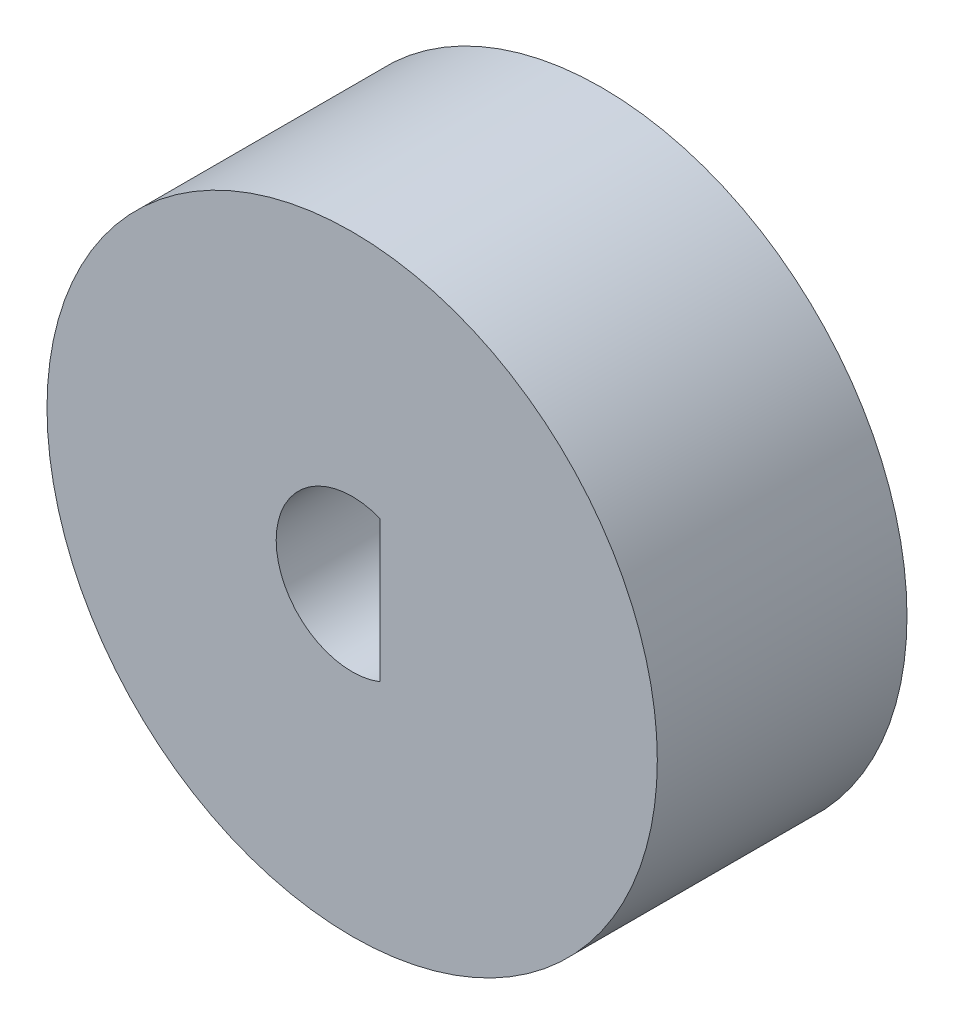
SolidWorks part; units mm, degrees
ref_plane "前视基准面" through (0, 0, 0) normal (0, 0, 1) x (1, 0, 0)
ref_plane "上视基准面" through (0, 0, 0) normal (0, 1, 0) x (1, 0, 0)
ref_plane "右视基准面" through (0, 0, 0) normal (1, 0, 0) x (0, 0, -1)
other "Configuration Table"
sketch "草图1" plane through (0, 0, 0) normal (0, 0, 1) x (1, 0, 0)
  line L0 (2, -5.1) -> (2, 5.1)
  circle A0 centre (0, 0) radius 22
  arc A1 (2, 5.1) -> (2, -5.1) centre (0, 0) ccw
extrude "凸台-拉伸1" add sketch "草图1" along normal blind 18
